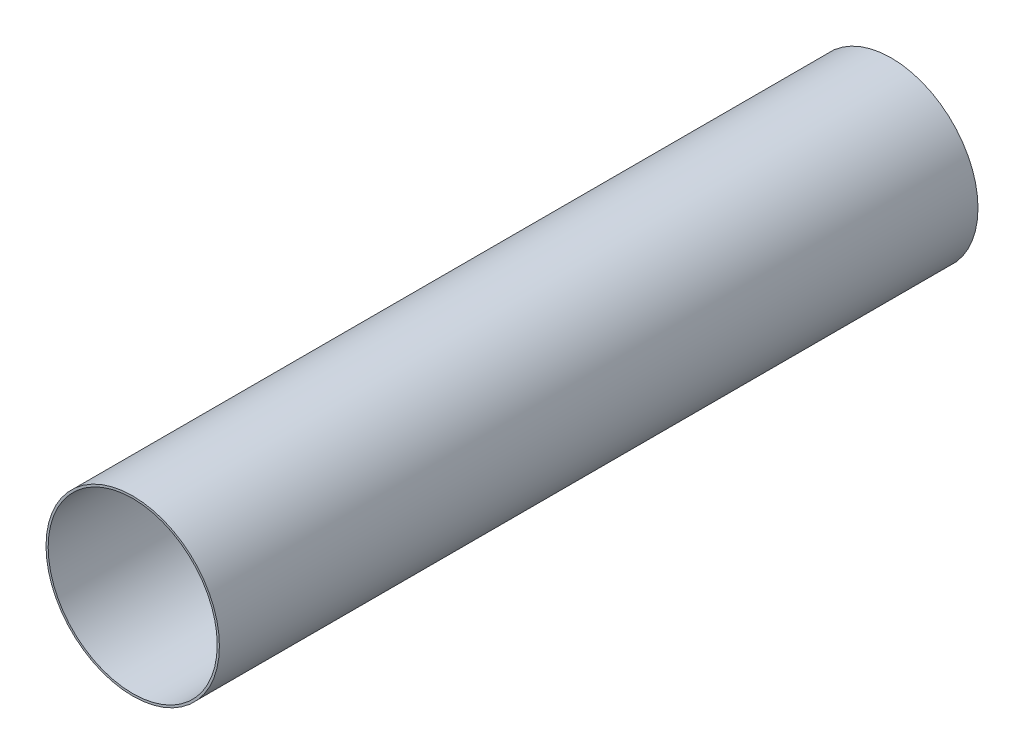
SolidWorks part; units mm, degrees
material "PVC Rigid"
ref_plane "Front Plane" through (0, 0, 0) normal (0, 0, 1) x (1, 0, 0)
ref_plane "Top Plane" through (0, 0, 0) normal (0, 1, 0) x (1, 0, 0)
ref_plane "Right Plane" through (0, 0, 0) normal (1, 0, 0) x (0, 0, -1)
sketch "Sketch1" plane through (0, 0, 0) normal (0, 0, 1) x (1, 0, 0)
  circle A0 centre (0, 0) radius 80
  circle A1 centre (0, 0) radius 78
  dimension "D1" = 160
  dimension "D2" = 2
extrude "Boss-Extrude1" add sketch "Sketch1" along normal blind 700
ref_plane "Plane1" through (0, 0, 350) normal (0, 0, 1) x (1, 0, 0)
